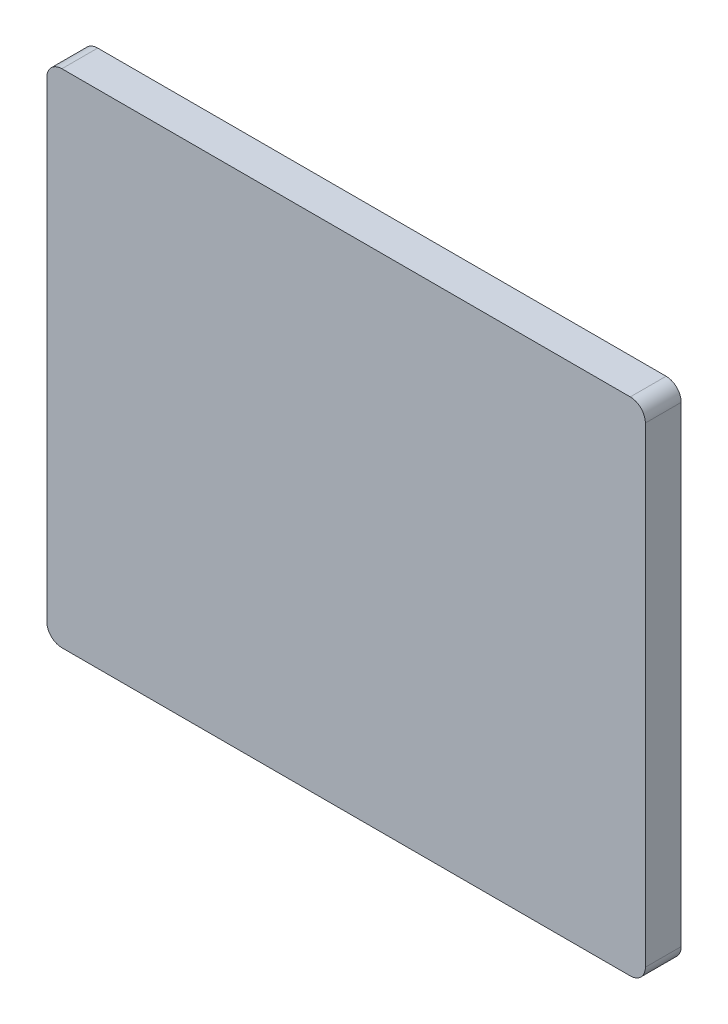
SolidWorks part; units mm, degrees
ref_plane "Plano frontal" through (0, 0, 0) normal (0, 0, 1) x (1, 0, 0)
ref_plane "Plano superior" through (0, 0, 0) normal (0, 1, 0) x (1, 0, 0)
ref_plane "Plano direito" through (0, 0, 0) normal (1, 0, 0) x (0, 0, -1)
sketch "Sketch1" plane through (0, 0, 0) normal (0, 0, 1) x (1, 0, 0)
  line L1 (15.875, -13.3) -> (-15.875, -13.3)
  line L2 (15.875, -13.3) -> (15.875, 13.3)
  line L3 (15.875, 13.3) -> (-15.875, 13.3)
  line L4 (-15.875, -13.3) -> (-15.875, 13.3)
  line L5 (15.875, -13.3) -> (-15.875, 13.3) construction
  line L6 (15.875, 13.3) -> (-15.875, -13.3) construction
  point P0 (0, 0)
  dimension "D1" = 31.75
  dimension "D2" = 26.6
extrude "Boss-Extrude1" add sketch "Sketch1" along normal blind 1.9
fillet "Fillet1" radius 0.8 4 edges at (-15.875, 13.3, 0.95) (15.875, 13.3, 0.95) (15.875, -13.3, 0.95) (-15.875, -13.3, 0.95)
